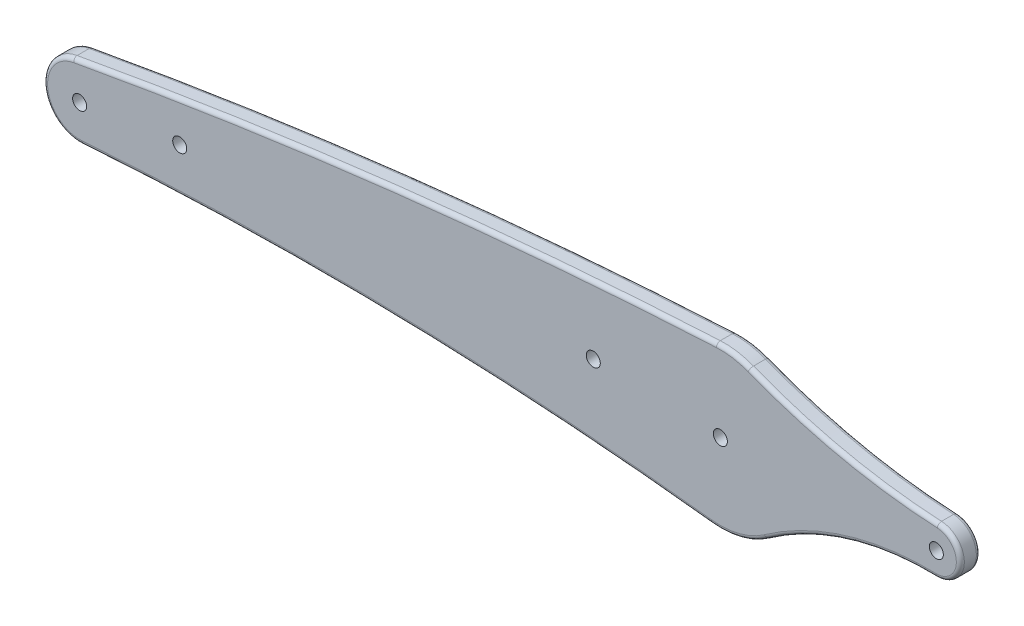
SolidWorks part; units mm, degrees
ref_plane "Front Plane" through (0, 0, 0) normal (0, 0, 1) x (1, 0, 0)
ref_plane "Top Plane" through (0, 0, 0) normal (0, 1, 0) x (1, 0, 0)
ref_plane "Right Plane" through (0, 0, 0) normal (1, 0, 0) x (0, 0, -1)
sketch "Sketch1" plane through (0, 0, 0) normal (0, 0, 1) x (1, 0, 0)
  line L0 (0, 0) -> (0, 28420.5788) construction
  line L1 (0, 0) -> (-28420.5788, 0) construction
  line L2 (-23, 10) -> (-28, 10)
  line L3 (-23, 0) -> (23, 0)
  line L4 (-23, 0) -> (-23, 10)
  line L5 (-23, 10) -> (23, 10)
  line L6 (23, 0) -> (23, 10)
  line L7 (-28, 10) -> (-41.8608, 50.4677)
  line L8 (-24.6313, 80.3256) -> (15.2446, 88.1625)
  line L9 (23, 10) -> (28, 10)
  line L10 (28, 10) -> (39.4051, 19.57)
  line L11 (39.4051, 19.57) -> (39.4051, 38.57)
  line L12 (39.4051, 38.57) -> (22.9346, 83.8223)
  line L13 (-20.22, 57.88) -> (7.2073, 203.3164) construction
  line L14 (16.5541, 81.5) -> (43.9813, 226.9364) construction
  line L15 (-27.5657, 229.7942) -> (7.2073, 203.3164) construction
  line L16 (7.2073, 203.3164) -> (43.9813, 226.9364) construction
  line L17 (43.9813, 226.9364) -> (-27.5657, 229.7942) construction
  line L18 (-27.5657, 229.7942) -> (-187.2585, 219.8842) construction
  line L19 (-152.8522, 195.7967) -> (61.1478, 205.8505) construction
  line L20 (-187.2585, 219.8842) -> (-152.8522, 195.7967) construction
  line L21 (-152.8522, 195.7967) -> (-207.7687, 192.7672) construction
  line L22 (-207.7687, 192.7672) -> (-187.2585, 219.8842) construction
  line L23 (-20.22, 57.88) -> (32.9338, 48.3578)
  line L24 (32.9338, 48.3578) -> (61.1478, 205.8505)
  circle A0 centre (-20.22, 57.88) radius 22.875 construction
  circle A1 centre (16.5541, 81.5) radius 6.79 construction
  arc A2 (-41.8608, 50.4677) -> (-24.6313, 80.3256) centre (-20.22, 57.88) cw
  arc A3 (15.2446, 88.1625) -> (22.9346, 83.8223) centre (16.5541, 81.5) cw
  circle A4 centre (-20.22, 57.88) radius 17.5 construction
  circle A5 centre (16.5541, 81.5) radius 7.5 construction
  circle A6 centre (7.2073, 203.3164) radius 13.1881 construction
  circle A7 centre (43.9813, 226.9364) radius 8.7345 construction
  circle A8 centre (-27.5657, 229.7942) radius 8.7345 construction
  circle A9 centre (-187.2585, 219.8842) radius 8.1525 construction
  circle A10 centre (-152.8522, 195.7967) radius 9.1166 construction
  dimension "D7" = 45.75
  dimension "D8" = 13.58
  dimension "D14" = 35
  dimension "D15" = 15
  dimension "D1" = 46
  dimension "D2" = 10
  dimension "D3" = 57.88
  dimension "D4" = 20.22
  dimension "D5" = 16.5541
  dimension "D6" = 81.5
  dimension "D9" = 5
  dimension "D10" = 5
  dimension "D11" = 140
  dimension "D12" = 19
  dimension "D13" = 160
  dimension "D16" = 148
  dimension "D17" = 110
  dimension "D18" = 160
  dimension "D19" = 54
  dimension "D20" = 214
  dimension "D21" = 42
  dimension "D22" = 34
  dimension "D23" = 55
  dimension "D24" = 54
  dimension "D25" = 160
sketch "Sketch2" plane through (0, 0, 0) normal (0, 0, 1) x (1, 0, 0)
  line L0 (-152.8522, 195.7967) -> (61.1478, 205.8505) construction
  line L1 (-152.8522, 195.7967) -> (61.1478, 205.8505) construction
  circle A0 centre (7.2073, 203.3164) radius 20
  circle A1 centre (7.2073, 203.3164) radius 10
  circle A2 centre (61.1478, 205.8505) radius 6
  circle A3 centre (-152.8522, 195.7967) radius 9
  arc A4 (-154.4656, 204.6509) -> (6.1924, 223.2906) centre (69.6216, -1025.099) cw
  arc A5 (-152.2126, 186.8195) -> (4.9312, 183.4463) centre (-91.8039, -661.0312) cw
  arc A6 (14.4893, 221.9436) -> (61.4538, 211.8427) centre (69.1045, 361.6475) ccw
  arc A7 (18.7678, 186.996) -> (60.9964, 199.8525) centre (59.2297, 129.8748) cw
  arc A8 (-152.8522, 195.7967) -> (7.2073, 203.3164) centre (-35.9399, -585.5045) cw construction
  circle A9 centre (-24.5427, 204.4133) radius 1.75
  circle A10 centre (-127.8522, 199.1306) radius 1.75
  circle A11 centre (-152.8522, 195.7967) radius 1.75
  circle A12 centre (61.1478, 205.8505) radius 1.75
  circle A13 centre (7.2073, 203.3164) radius 1.75
  point P2 (7.2073, 203.3164)
  dimension "D1" = 40
  dimension "D2" = 20
  dimension "D3" = 12
  dimension "D4" = 18
  dimension "D5" = 1250
  dimension "D6" = 850
  dimension "D7" = 150
  dimension "D8" = 70
  dimension "D9" = 790
  dimension "D12" = 3.5
  dimension "D13" = 3.5
  dimension "D10" = 31.75
  dimension "D11" = 25
extrude "Boss-Extrude1" add sketch "Sketch2" along normal mid plane 5 contours A3 A5 A0 A4 A10 A9 | A3 A11 | A0 A1 | A1 A13 | A2 A12 | A0 A7 A2 A6
fillet "Fillet1" radius 1 16 edges at (-161.7812, 194.6685, -2.5) (-161.7812, 194.6685, 2.5) (-73.5626, 188.773, -2.5) (-73.5626, 188.773, 2.5) (12.1772, 183.9437, -2.5) (12.1772, 183.9437, 2.5) (38.8422, 196.84, -2.5) (38.8422, 196.84, 2.5) (67.1434, 205.6218, -2.5) (67.1434, 205.6218, 2.5) (37.5646, 215.0009, -2.5) (37.5646, 215.0009, 2.5) (10.4124, 223.0579, -2.5) (10.4124, 223.0579, 2.5) (-74.4384, 216.5719, -2.5) (-74.4384, 216.5719, 2.5)
